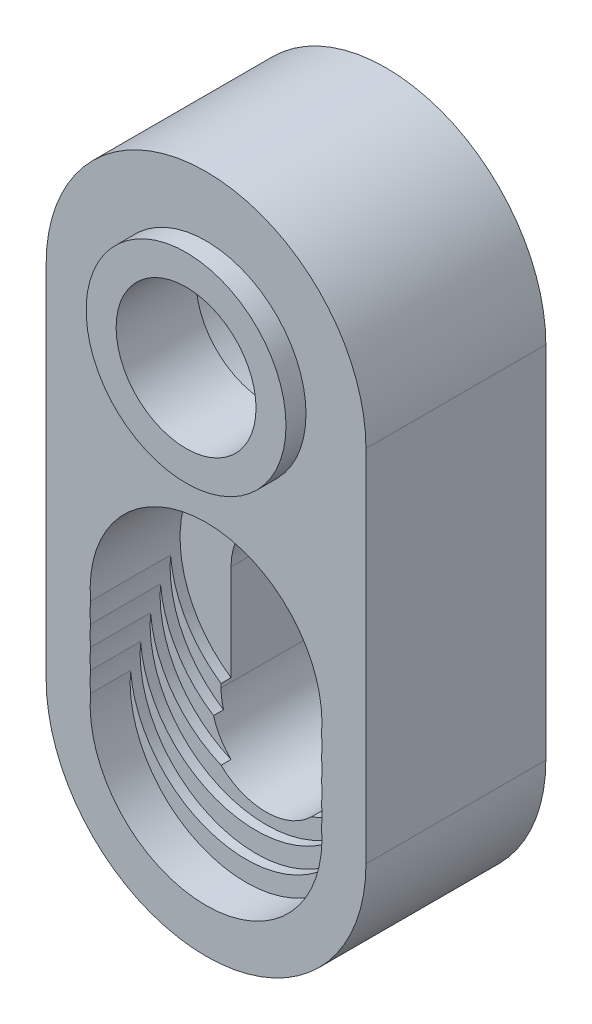
SolidWorks part; units mm, degrees
ref_plane "Plano frontal" through (0, 0, 0) normal (0, 0, 1) x (1, 0, 0)
ref_plane "Plano superior" through (0, 0, 0) normal (0, 1, 0) x (1, 0, 0)
ref_plane "Plano direito" through (0, 0, 0) normal (1, 0, 0) x (0, 0, -1)
sketch "Esboço1" plane through (0, 0, 0) normal (0, 0, 1) x (1, 0, 0)
  line L0 (-4, 0) -> (-4, -9)
  line L1 (4, 0) -> (4, -9)
  circle A0 centre (0, 0) radius 1.75
  arc A1 (4, 0) -> (-4, 0) centre (0, 0) ccw
  arc A2 (-4, -9) -> (4, -9) centre (0, -9) ccw
  dimension "D1" = 8
  dimension "D2" = 8
  dimension "D3" = 3.5
  dimension "D4" = 9
extrude "Ressalto-extrusão1" add sketch "Esboço1" along normal blind 4.5
sketch "Esboço2" plane through (0, 0, 4.5) normal (0, 0, 1) x (1, 0, 0)
  circle A0 centre (0, 0) radius 1.75
  circle A1 centre (0, 0) radius 2.5
  dimension "D1" = 5
extrude "Ressalto-extrusão2" add sketch "Esboço2" along normal blind 0.5
sketch "Esboço3" plane through (0, 0, 4.5) normal (0, 0, 1) x (1, 0, 0)
  line L0 (-1.625, -6.5) -> (-1.625, -9)
  line L1 (1.625, -6.5) -> (1.625, -9)
  arc A0 (1.625, -6.5) -> (-1.625, -6.5) centre (0, -6.5) ccw
  arc A1 (-1.625, -9) -> (1.625, -9) centre (0, -9) ccw
  arc A2 (-4, -9) -> (4, -9) centre (0, -9) ccw construction
  dimension "D1" = 3.25
  dimension "D2" = 3.25
  dimension "D3" = 0
  dimension "D4" = 6.5
extrude "Corte-extrusão1" cut sketch "Esboço3" against normal through all
sketch "Esboço4" plane through (0, 0, 4.5) normal (0, 0, 1) x (1, 0, 0)
  circle A0 centre (0, -9) radius 2.9
  dimension "D1" = 5.8
extrude "Corte-extrusão2" cut sketch "Esboço4" against normal blind 1
sketch "Esboço5" plane through (0, 0, 4.5) normal (0, 0, 1) x (1, 0, 0)
  circle A0 centre (0, -8.5) radius 2.9
  arc A1 (-1.625, -6.598) -> (1.625, -6.598) centre (0, -9) ccw construction
  dimension "D1" = 5.8
  dimension "D2" = 0.5
extrude "Corte-extrusão3" cut sketch "Esboço5" against normal blind 1.25
sketch "Esboço6" plane through (0, 0, 4.5) normal (0, 0, 1) x (1, 0, 0)
  circle A0 centre (0, -8) radius 2.9
  arc A1 (2.8892, -8.75) -> (1.5636, -6.0577) centre (0, -8.5) ccw construction
  dimension "D1" = 5.8
  dimension "D2" = 0.5
extrude "Corte-extrusão4" cut sketch "Esboço6" against normal blind 1.5
sketch "Esboço7" plane through (0, 0, 4.5) normal (0, 0, 1) x (1, 0, 0)
  circle A0 centre (0, -7.5) radius 2.9
  arc A1 (-1.1245, -5.3269) -> (1.1245, -5.3269) centre (0, -8) ccw construction
  dimension "D1" = 5.8
  dimension "D2" = 0.5
extrude "Corte-extrusão5" cut sketch "Esboço7" against normal blind 1.75
sketch "Esboço8" plane through (0, 0, 4.5) normal (0, 0, 1) x (1, 0, 0)
  circle A0 centre (0, -7) radius 2.9
  arc A1 (1.1245, -10.1731) -> (-1.1245, -10.1731) centre (0, -7.5) ccw construction
  dimension "D1" = 0.5
  dimension "D2" = 5.8
extrude "Corte-extrusão6" cut sketch "Esboço8" against normal blind 2
sketch "Esboço9" plane through (0, 0, 4.5) normal (0, 0, 1) x (1, 0, 0)
  circle A0 centre (0, -6.5) radius 2.9
  arc A1 (1.5636, -9.4423) -> (-1.5636, -9.4423) centre (0, -7) ccw construction
  dimension "D1" = 5.8
  dimension "D2" = 0.5
extrude "Corte-extrusão7" cut sketch "Esboço9" against normal blind 2.25
sketch "Esboço10" plane through (0, 0, 0) normal (0, 0, -1) x (-1, 0, 0)
  circle A0 centre (0, 0) radius 2.9
  dimension "D1" = 5.8
extrude "Corte-extrusão8" cut sketch "Esboço10" against normal blind 3
